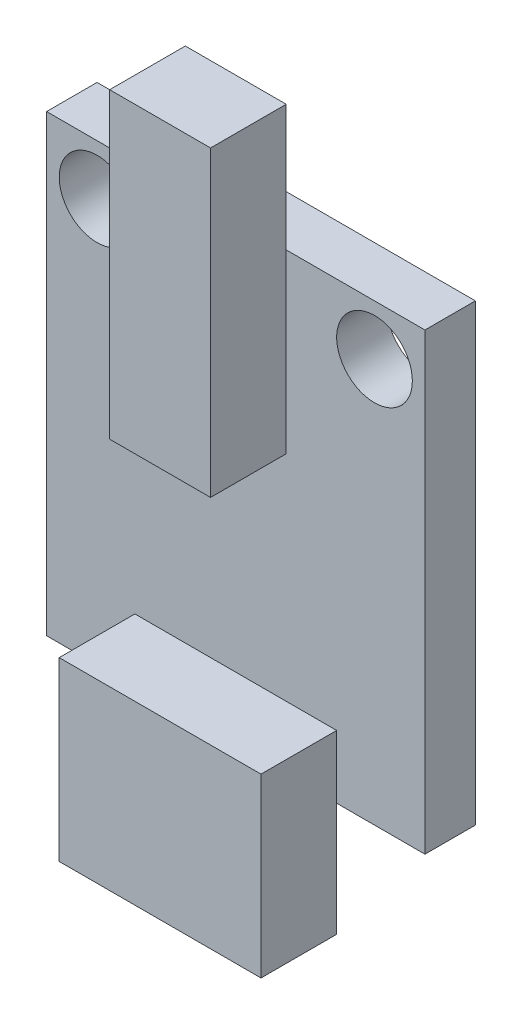
SolidWorks part; units mm, degrees
ref_plane "Alzado" through (0, 0, 0) normal (0, 0, 1) x (1, 0, 0)
ref_plane "Planta" through (0, 0, 0) normal (0, 1, 0) x (1, 0, 0)
ref_plane "Vista lateral" through (0, 0, 0) normal (1, 0, 0) x (0, 0, -1)
sketch "Croquis1" plane through (0, 0, 0) normal (0, 0, 1) x (1, 0, 0)
  line L1 (-7.5, 9) -> (7.5, 9)
  line L2 (-7.5, 9) -> (-7.5, -9)
  line L3 (-7.5, -9) -> (7.5, -9)
  line L4 (7.5, 9) -> (7.5, -9)
  line L5 (-7.5, 9) -> (7.5, -9) construction
  line L6 (-7.5, -9) -> (7.5, 9) construction
  point P0 (0, 0)
  dimension "D1" = 15
  dimension "D2" = 18
extrude "Saliente-Extruir1" add sketch "Croquis1" along normal blind 2
sketch "Croquis2" plane through (0, 0, 2) normal (0, 0, 1) x (1, 0, 0)
  line L0 (-7.5, 7) -> (7.5, 7) construction
  line L1 (-7.5, 9) -> (-7.5, -9) construction
  line L2 (7.5, -9) -> (7.5, 9) construction
  line L3 (7.5, 9) -> (-7.5, 9) construction
  circle A0 centre (-5.5, 7) radius 1.5
  circle A1 centre (5.5, 7) radius 1.5
  dimension "D1" = 3
  dimension "D2" = 3
  dimension "D4" = 2
  dimension "D5" = 2
  dimension "D3" = 2
extrude "Cortar-Extruir1" cut sketch "Croquis2" against normal through all
sketch "Croquis3" plane through (0, 0, 2) normal (0, 0, 1) x (1, 0, 0)
  line L1 (-2, 14) -> (2, 14)
  line L2 (-2, 14) -> (-2, 2)
  line L3 (-2, 2) -> (2, 2)
  line L4 (2, 14) -> (2, 2)
  dimension "D1" = 4
  dimension "D2" = 12
  dimension "D3" = 2
  dimension "D4" = 2
extrude "Saliente-Extruir2" add sketch "Croquis3" along normal blind 3
sketch "Croquis4" plane through (0, 0, 2) normal (0, 0, 1) x (1, 0, 0)
  line L0 (-7.5, -9) -> (7.5, -9) construction
  line L1 (-4, -6.5) -> (4, -6.5)
  line L2 (-4, -6.5) -> (-4, -13.5)
  line L3 (-4, -13.5) -> (4, -13.5)
  line L4 (4, -6.5) -> (4, -13.5)
  dimension "D1" = 8
  dimension "D2" = 7
  dimension "D3" = 2.5
  dimension "D4" = 4
extrude "Saliente-Extruir3" add sketch "Croquis4" along normal blind 3
